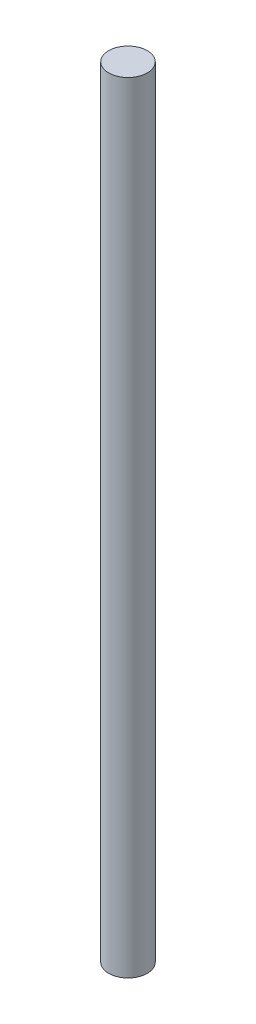
SolidWorks part; units mm, degrees
material "ASTM A36 Steel"
ref_plane "Front Plane" through (0, 0, 0) normal (0, 0, 1) x (1, 0, 0)
ref_plane "Top Plane" through (0, 0, 0) normal (0, 1, 0) x (1, 0, 0)
ref_plane "Right Plane" through (0, 0, 0) normal (1, 0, 0) x (0, 0, -1)
sketch "Sketch1" plane through (0, 0, 0) normal (0, 1, 0) x (1, 0, 0)
  circle A0 centre (0, 0) radius 7.5
extrude "Boss-Extrude1" add sketch "Sketch1" along normal blind 303
